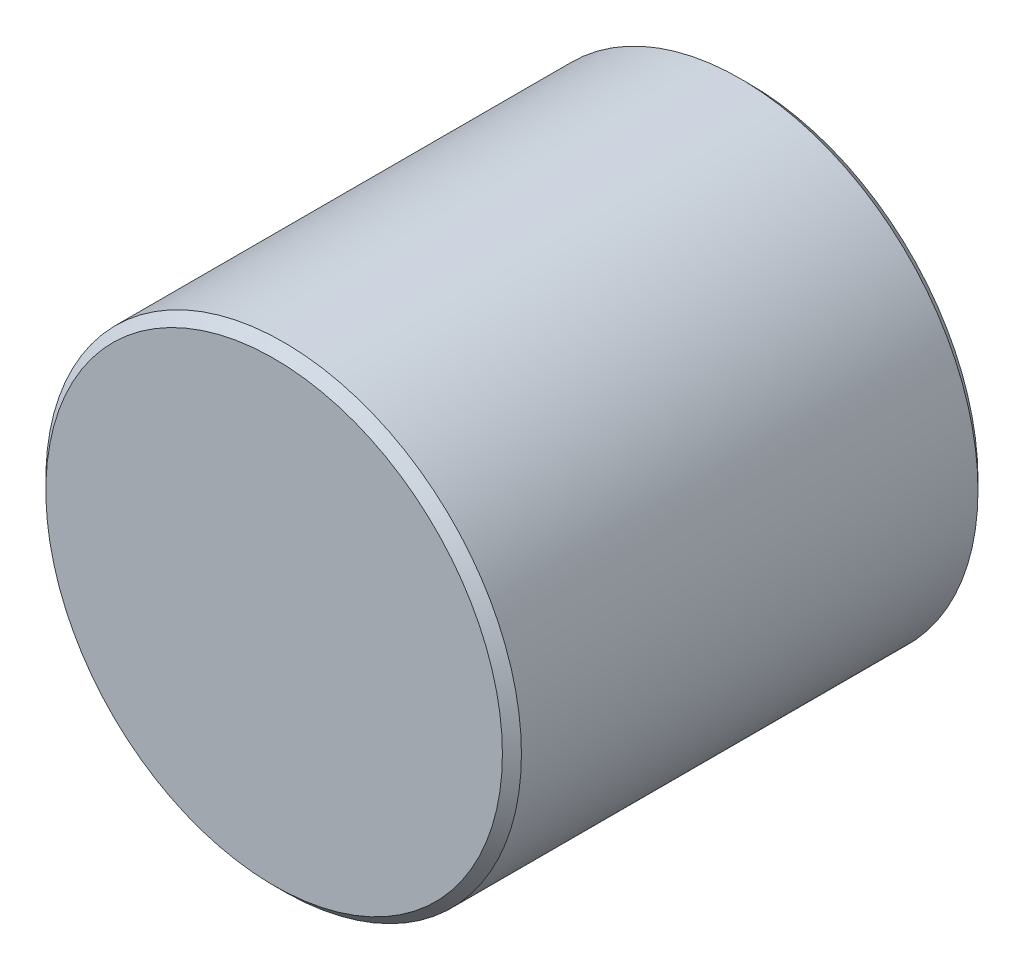
SolidWorks part; units mm, degrees
ref_plane "Front Plane" through (0, 0, 0) normal (0, 0, 1) x (1, 0, 0)
ref_plane "Top Plane" through (0, 0, 0) normal (0, 1, 0) x (1, 0, 0)
ref_plane "Right Plane" through (0, 0, 0) normal (1, 0, 0) x (0, 0, -1)
sketch "Sketch1" plane through (0, 0, 0) normal (0, 0, 1) x (1, 0, 0)
  circle A0 centre (0, 0) radius 2.5
  dimension "D1" = 5
extrude "Boss-Extrude1" add sketch "Sketch1" along normal blind 5
chamfer "Chamfer1" distance 0.1 angle 45 2 edges at (2.5, 0, 0) (2.5, 0, 5)
